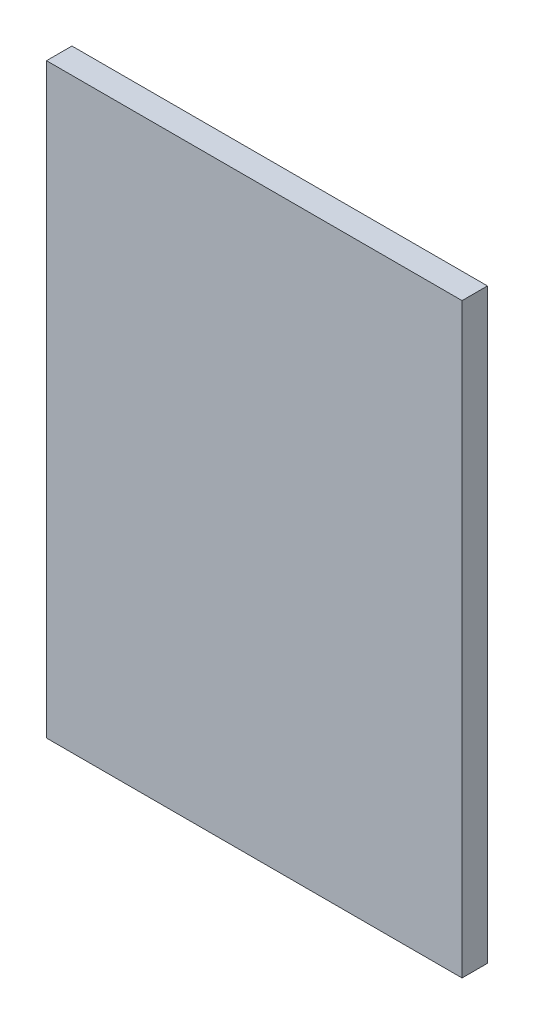
SolidWorks part; units mm, degrees
ref_plane "Front Plane" through (0, 0, 0) normal (0, 0, 1) x (1, 0, 0)
ref_plane "Top Plane" through (0, 0, 0) normal (0, 1, 0) x (1, 0, 0)
ref_plane "Right Plane" through (0, 0, 0) normal (1, 0, 0) x (0, 0, -1)
sketch "Sketch1" plane through (0, 0, 0) normal (0, 0, 1) x (1, 0, 0)
  line L1 (26.9875, -38.1) -> (-26.9875, -38.1)
  line L2 (26.9875, -38.1) -> (26.9875, 38.1)
  line L3 (26.9875, 38.1) -> (-26.9875, 38.1)
  line L4 (-26.9875, -38.1) -> (-26.9875, 38.1)
  line L5 (26.9875, -38.1) -> (-26.9875, 38.1) construction
  line L6 (26.9875, 38.1) -> (-26.9875, -38.1) construction
  point P0 (0, 0)
  dimension "D1" = 53.975
  dimension "D2" = 76.2
extrude "Boss-Extrude1" add sketch "Sketch1" along normal blind 3.302
equation "\"thick\"= 0.125in"
equation "\"D1@Sketch1\"=2+\"thick\" "
